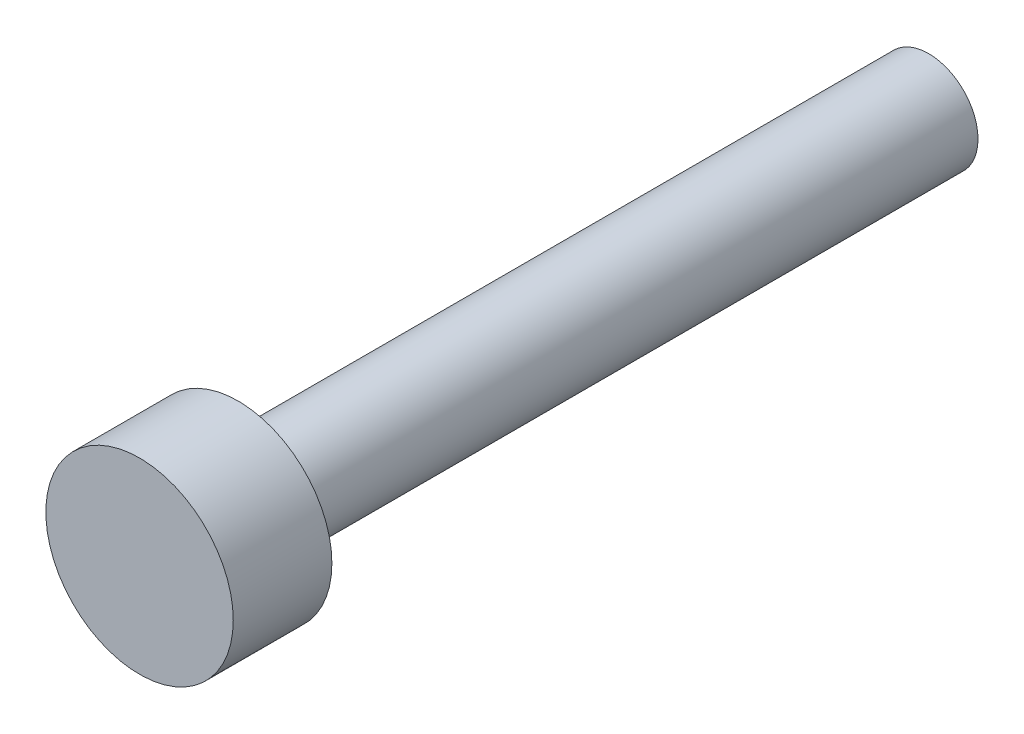
SolidWorks part; units mm, degrees
ref_plane "Front Plane" through (0, 0, 0) normal (0, 0, 1) x (1, 0, 0)
ref_plane "Top Plane" through (0, 0, 0) normal (0, 1, 0) x (1, 0, 0)
ref_plane "Right Plane" through (0, 0, 0) normal (1, 0, 0) x (0, 0, -1)
sketch "Shank_nominal_thread_envelope_profile" plane through (0, 0, 0) normal (0, 0, 1) x (1, 0, 0)
  circle A0 centre (0, 0) radius 1
  dimension "D1" = 2
extrude "Shank_nominal_thread_envelope" add sketch "Shank_nominal_thread_envelope_profile" along normal blind 14 from offset 14
sketch "Socket_head_envelope_profile" plane through (0, 0, 0) normal (0, 0, 1) x (1, 0, 0)
  circle A0 centre (0, 0) radius 1.9
  dimension "D1" = 3.8
extrude "Socket_head_envelope" add sketch "Socket_head_envelope_profile" along normal blind 2
